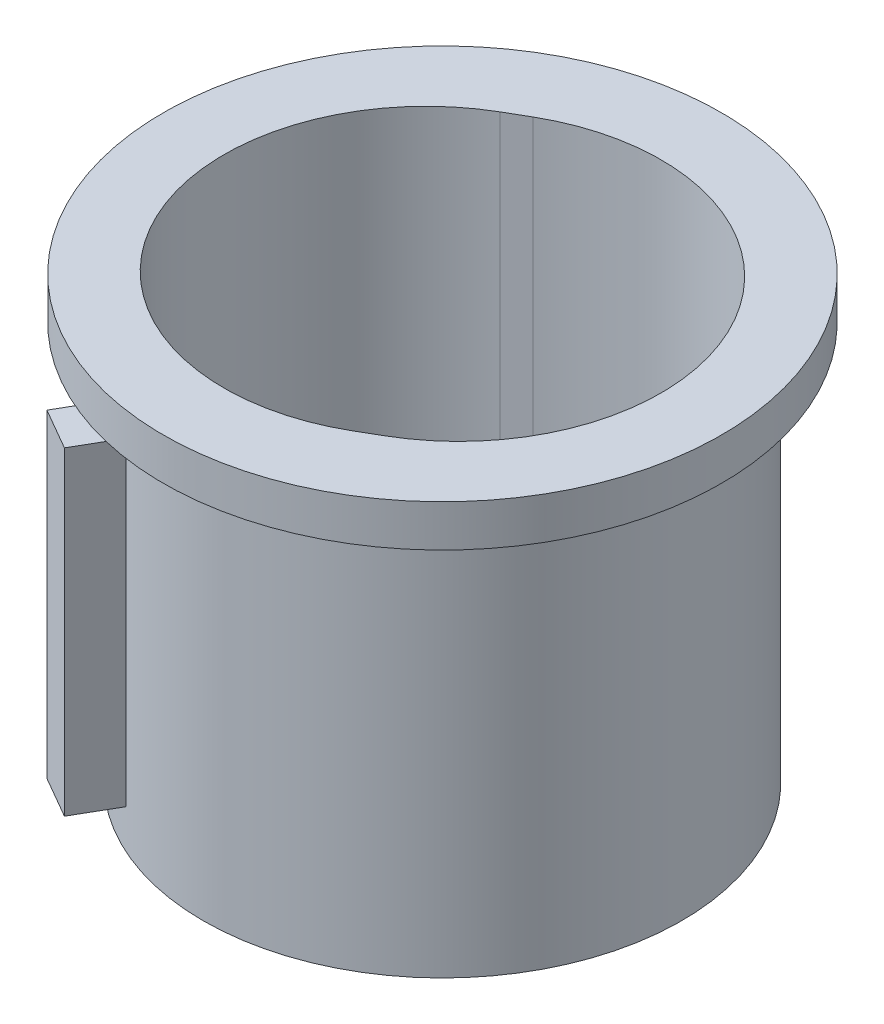
SolidWorks part; units mm, degrees
other "Acetal Torque Guide Bush Relieved"
ref_plane "Front Plane" through (0, 0, 0) normal (0, 0, 1) x (1, 0, 0)
ref_plane "Top Plane" through (0, 0, 0) normal (0, 1, 0) x (1, 0, 0)
ref_plane "Right Plane" through (0, 0, 0) normal (1, 0, 0) x (0, 0, -1)
sketch3d "Guide bush barrel sketch datum points"
  point P0 (-20.2917, -105.98, 0)
  point P1 (-10.2917, -105.98, 0)
  point P2 (-20.2917, -105.98, -10)
ref_plane "Guide bush barrel sketch plane" through (0, -105.98, 0) normal (0, 1, 0) x (1, 0, 0)
sketch "Guide bush barrel sketch" plane through (0, -105.98, 0) normal (0, 1, 0) x (1, 0, 0)
  circle A0 centre (-20.2917, 0) radius 6
extrude "Guide bush barrel" add sketch "Guide bush barrel sketch" along normal blind 10 separate body
sketch3d "Guide bush flange sketch datum points"
  point P0 (-20.2917, -95.98, 0)
  point P1 (-10.2917, -95.98, 0)
  point P2 (-20.2917, -95.98, -10)
ref_plane "Guide bush flange sketch plane" through (0, -95.98, 0) normal (0, 1, 0) x (1, 0, 0)
sketch "Guide bush flange sketch" plane through (0, -95.98, 0) normal (0, 1, 0) x (1, 0, 0)
  circle A0 centre (-20.2917, 0) radius 7
extrude "Guide bush flange" add sketch "Guide bush flange sketch" along normal blind 1.05
sketch3d "Directional running slot sketch datum points"
  point P0 (-20.2917, -106.08, 0)
  point P1 (-10.2917, -106.08, 0)
  point P2 (-20.2917, -106.08, -10)
ref_plane "Directional running slot sketch plane" through (0, -106.08, 0) normal (0, 1, 0) x (1, 0, 0)
sketch "Directional running slot sketch" plane through (0, -106.08, 0) normal (0, 1, 0) x (1, 0, 0)
  line L0 (-23.0865, -4.2407) -> (-22.5668, -4.5407)
  line L1 (-17.4968, 4.2407) -> (-18.0165, 4.5407)
  arc A0 (-22.5668, -4.5407) -> (-17.4968, 4.2407) centre (-20.0318, -0.15) ccw
  arc A1 (-18.0165, 4.5407) -> (-23.0865, -4.2407) centre (-20.5515, 0.15) ccw
extrude "Directional running slot" cut sketch "Directional running slot sketch" along normal blind 11.25
sketch3d "Antirotation guide key sketch datum points"
  point P0 (-20.2917, -105, 0)
  point P1 (-10.2917, -105, 0)
  point P2 (-20.2917, -105, -10)
ref_plane "Antirotation guide key sketch plane" through (0, -105, 0) normal (0, 1, 0) x (1, 0, 0)
sketch "Antirotation guide key sketch" plane through (0, -105, 0) normal (0, 1, 0) x (1, 0, 0)
  line L0 (-14.4917, -0.6) -> (-13.1917, -0.6)
  line L1 (-13.1917, -0.6) -> (-13.1917, 0.6)
  line L2 (-13.1917, 0.6) -> (-14.4917, 0.6)
  line L3 (-14.4917, 0.6) -> (-14.4917, -0.6)
extrude "Antirotation guide key" add sketch "Antirotation guide key sketch" along normal blind 8
move or copy body "Move1" bodies to move or copy 104 copy no translate (56.2917, 0, 0) parameters "D1"=56.2917, "D2"=0, "D3"=0
move or copy body "Move2" bodies to move or copy 105 copy no rotation origin (0, 0, 0) rotation axis (0, -1, 0) rotation angle 120
move or copy body "Move3" bodies to move or copy 106 copy no translate (-56.2917, 0, 0) parameters "D1"=56.2917, "D2"=0, "D3"=0
